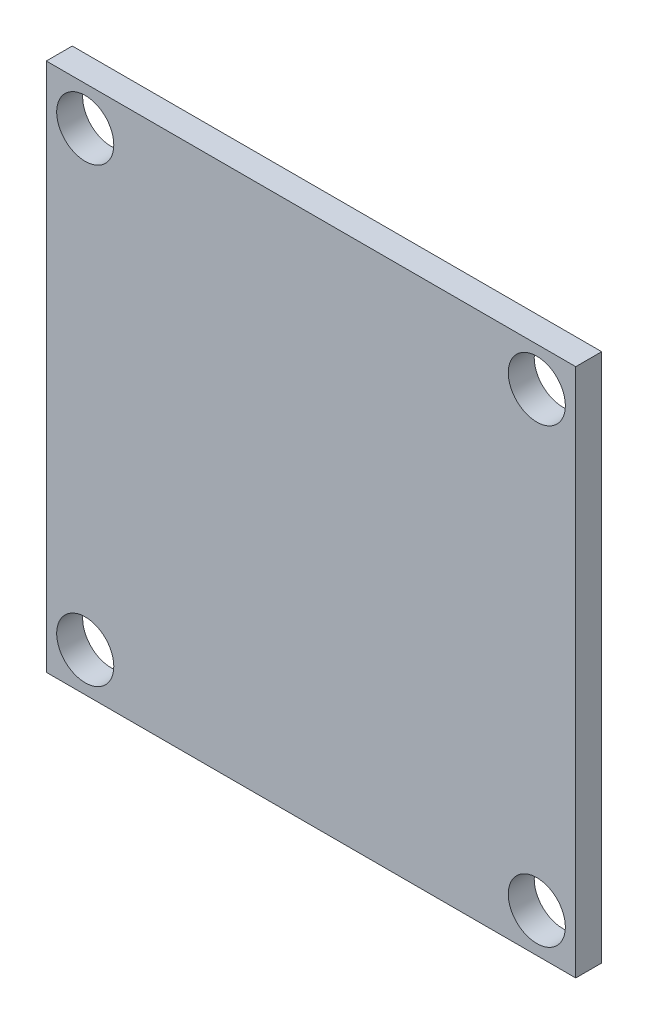
SolidWorks part; units mm, degrees
ref_plane "Front Plane" through (0, 0, 0) normal (0, 0, 1) x (1, 0, 0)
ref_plane "Top Plane" through (0, 0, 0) normal (0, 1, 0) x (1, 0, 0)
ref_plane "Right Plane" through (0, 0, 0) normal (1, 0, 0) x (0, 0, -1)
sketch "Sketch1" plane through (0, 0, 0) normal (0, 0, 1) x (1, 0, 0)
  line L1 (-25.908, -25.908) -> (25.908, -25.908)
  line L2 (-25.908, -25.908) -> (-25.908, 25.908)
  line L3 (-25.908, 25.908) -> (25.908, 25.908)
  line L4 (25.908, -25.908) -> (25.908, 25.908)
  line L5 (-25.908, -25.908) -> (25.908, 25.908) construction
  line L6 (-25.908, 25.908) -> (25.908, -25.908) construction
  point P0 (0, 0)
  dimension "D1" = 51.816
  dimension "D2" = 51.816
extrude "Boss-Extrude1" add sketch "Sketch1" along normal blind 2.54
sketch "Sketch2" plane through (0, 0, 2.54) normal (0, 0, 1) x (1, 0, 0)
  line L1 (22.098, 22.098) -> (-22.098, 22.098)
  line L2 (22.098, 22.098) -> (22.098, -22.098)
  line L3 (22.098, -22.098) -> (-22.098, -22.098)
  line L4 (-22.098, 22.098) -> (-22.098, -22.098)
  line L5 (22.098, 22.098) -> (-22.098, -22.098) construction
  line L6 (22.098, -22.098) -> (-22.098, 22.098) construction
  circle A0 centre (22.098, 22.098) radius 2.794
  circle A1 centre (22.098, -22.098) radius 2.794
  circle A2 centre (-22.098, 22.098) radius 2.794
  circle A3 centre (-22.098, -22.098) radius 2.794
  point P0 (0, 0)
  dimension "D3" = 5.588
  dimension "D4" = 5.588
  dimension "D5" = 5.588
  dimension "D6" = 5.588
  dimension "D1" = 44.196
  dimension "D2" = 44.196
extrude "Cut-Extrude1" cut sketch "Sketch2" against normal blind 5.08 contours A0 | A2 | A3 | A1
